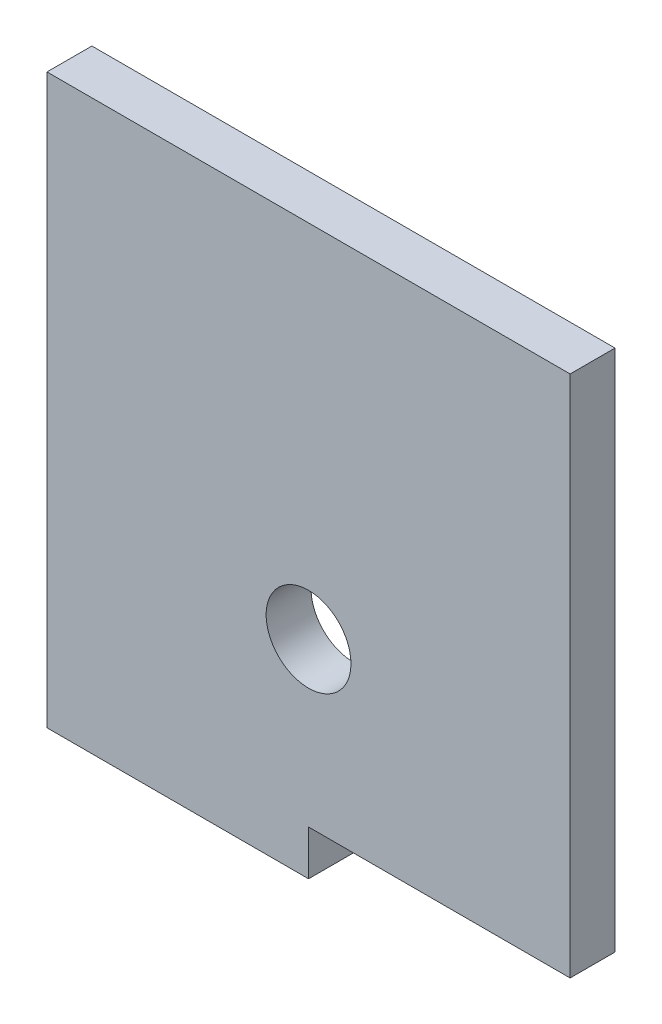
SolidWorks part; units mm, degrees
ref_plane "Front Plane" through (0, 0, 0) normal (0, 0, 1) x (1, 0, 0)
ref_plane "Top Plane" through (0, 0, 0) normal (0, 1, 0) x (1, 0, 0)
ref_plane "Right Plane" through (0, 0, 0) normal (1, 0, 0) x (0, 0, -1)
sketch "Sketch1" plane through (0, 0, 0) normal (0, 0, 1) x (1, 0, 0)
  line L0 (18.5, 0) -> (18.5, -3.175)
  line L1 (18.5, 0) -> (37, 0)
  line L2 (0, 0) -> (0, 37)
  line L3 (0, 37) -> (37, 37)
  line L4 (37, 0) -> (37, 37)
  line L5 (18.5, -3.175) -> (0, -3.175)
  line L6 (0, -3.175) -> (0, 0)
  line L7 (18.5, 0) -> (0, 0) construction
  line L10 (37, 0) -> (0, 37) construction
  circle A2 centre (18.5, 11.5) radius 2.5 construction
  circle A3 centre (18.5, 11.5) radius 3
  point P10 (19.4231, 0)
  dimension "D4" = 18.5
  dimension "D6" = 5
  dimension "D7" = 0.5
  dimension "D1" = 37
  dimension "D2" = 37
  dimension "D3" = 3.175
  dimension "D5" = 11.5
extrude "Boss-Extrude1" add sketch "Sketch1" along normal blind 3.175
